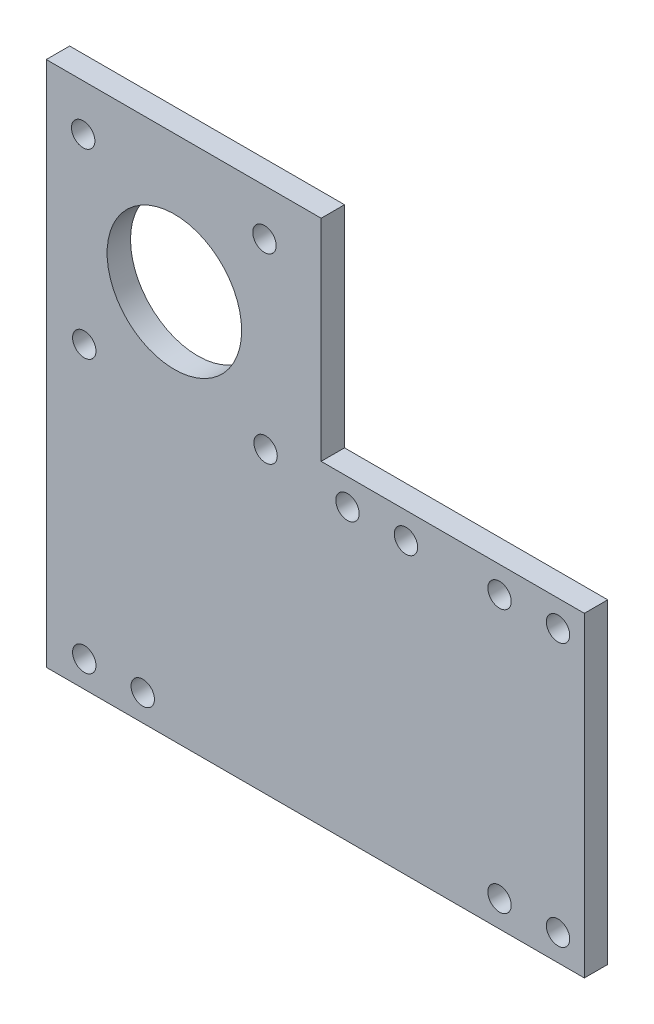
SolidWorks part; units mm, degrees
ref_plane "Front Plane" through (0, 0, 0) normal (0, 0, 1) x (1, 0, 0)
ref_plane "Top Plane" through (0, 0, 0) normal (0, 1, 0) x (1, 0, 0)
ref_plane "Right Plane" through (0, 0, 0) normal (1, 0, 0) x (0, 0, -1)
sketch "Sketch1" plane through (0, 0, 0) normal (0, 0, 1) x (1, 0, 0)
  line L0 (-45, 27) -> (-45, 63)
  line L1 (-45, -27) -> (45, -27)
  line L2 (-45, -27) -> (-45, 27)
  line L3 (0, 27) -> (45, 27)
  line L4 (45, -27) -> (45, 27)
  line L5 (-45, -27) -> (45, 27) construction
  line L6 (-45, 27) -> (45, -27) construction
  line L7 (-45, 63) -> (0, 63)
  line L8 (0, 63) -> (0, 27)
  point P0 (0, 0)
  dimension "D1" = 54
  dimension "D2" = 90
  dimension "D3" = 36
  dimension "D4" = 45
extrude "Boss-Extrude1" add sketch "Sketch1" along normal blind 4
sketch "Sketch2" plane through (0, 0, 4) normal (0, 0, 1) x (1, 0, 0)
  line L0 (-40.5, 22.5) -> (-40.5, -22.5) construction
  line L1 (-30.5, -22.5) -> (-40.5, -22.5) construction
  line L2 (-40.5, 22.5) -> (-30.5, 22.5) construction
  line L3 (-45, 63) -> (-45, -27) construction
  line L4 (45, 27) -> (0, 27) construction
  line L5 (-45, -27) -> (45, -27) construction
  line L6 (0, 0) -> (0, 15.5228) construction
  circle A2 centre (-40.5, -22.5) radius 2
  circle A3 centre (-30.5, -22.5) radius 2
  circle A4 centre (30.5, -22.5) radius 2
  circle A5 centre (40.5, -22.5) radius 2
  circle A6 centre (30.5, 22.5) radius 2
  circle A7 centre (40.5, 22.5) radius 2
  dimension "D4" = 10
  dimension "D1" = 4.5
  dimension "D2" = 4.5
  dimension "D3" = 4.5
  dimension "D5" = 10
  dimension "D6" = 10
extrude "Cut-Extrude1" cut sketch "Sketch2" against normal blind 4
sketch "Sketch3" plane through (0, 0, 4) normal (0, 0, 1) x (1, 0, 0)
  circle A0 centre (-40.5, 24.0809) radius 2
  circle A1 centre (-9.5, 24.0345) radius 2
  circle A3 centre (-40.5, -22.5) radius 2 construction
  dimension "D1" = 4
  dimension "D2" = 4
  dimension "D3" = 31
  dimension "D4" = 0
extrude "Cut-Extrude2" cut sketch "Sketch3" against normal blind 4
sketch "Sketch4" plane through (0, 0, 4) normal (0, 0, 1) x (1, 0, 0)
  line L0 (-40.5, 24.0809) -> (-40.6908, 55.0809) construction
  line L1 (-40.6908, 55.0809) -> (-9.6908, 55.0809) construction
  circle A0 centre (-40.6908, 55.0809) radius 2
  circle A1 centre (-9.6908, 55.0809) radius 2
  dimension "D3" = 4
  dimension "D1" = 31
  dimension "D2" = 31
extrude "Cut-Extrude3" cut sketch "Sketch4" against normal blind 4
sketch "Sketch5" plane through (0, 0, 4) normal (0, 0, 1) x (1, 0, 0)
  line L1 (-45, 63) -> (-47, 63)
  line L2 (-45, 63) -> (-45, -27)
  line L3 (-45, -27) -> (-47, -27)
  line L4 (-47, 63) -> (-47, -27)
  dimension "D1" = 2
extrude "Boss-Extrude2" add sketch "Sketch5" against normal blind 4
sketch "Sketch6" plane through (0, 0, 4) normal (0, 0, 1) x (1, 0, 0)
  line L0 (4.5, 22.5) -> (14.5, 22.5) construction
  line L1 (14.5, 22.5) -> (30.5, 22.5) construction
  line L3 (0, 27) -> (0, 63) construction
  circle A0 centre (4.5, 22.5) radius 2
  circle A1 centre (14.5, 22.5) radius 2
  dimension "D1" = 4
  dimension "D2" = 4
  dimension "D3" = 10
  dimension "D4" = 4.5
extrude "Cut-Extrude4" cut sketch "Sketch6" against normal blind 4
sketch "Sketch7" plane through (0, 0, 4) normal (0, 0, 1) x (1, 0, 0)
  line L0 (-40.6908, 55.0809) -> (-9.5, 24.0345) construction
  circle A0 centre (-25.0954, 39.5577) radius 11.5
  dimension "D1" = 23
extrude "Cut-Extrude5" cut sketch "Sketch7" against normal blind 10
